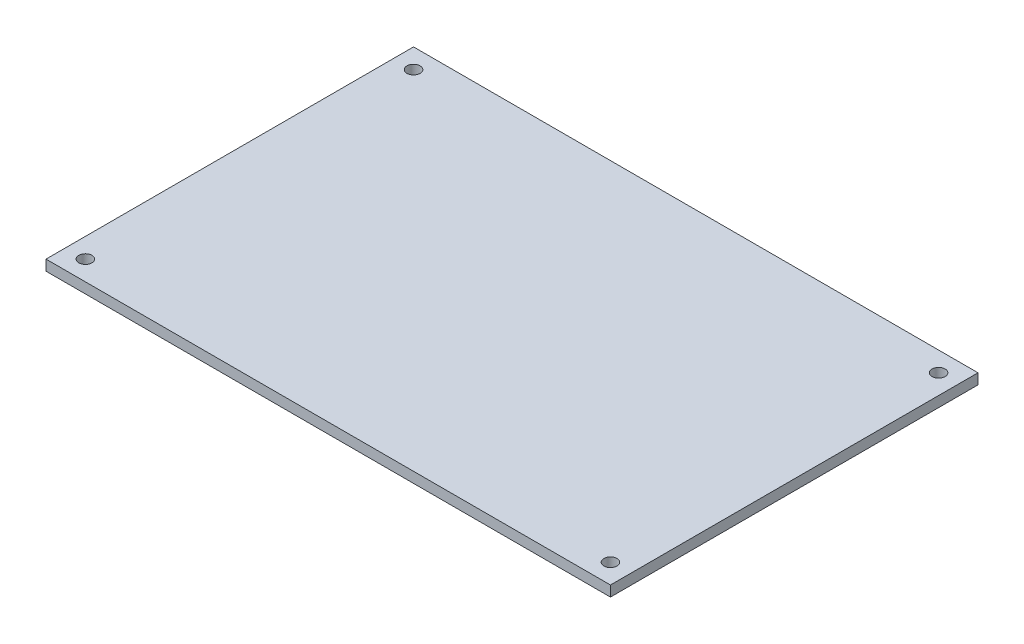
SolidWorks part; units mm, degrees
ref_plane "前视基准面" through (0, 0, 0) normal (0, 0, 1) x (1, 0, 0)
ref_plane "上视基准面" through (0, 0, 0) normal (0, 1, 0) x (1, 0, 0)
ref_plane "右视基准面" through (0, 0, 0) normal (1, 0, 0) x (0, 0, -1)
other "Configuration Table"
sketch "草图2" plane through (0, 0, 0) normal (0, 1, 0) x (1, 0, 0)
  line L0 (0, 28) -> (0, -28) construction
  line L1 (-43, -28) -> (43, -28)
  line L2 (-43, -28) -> (-43, 28)
  line L3 (-43, 28) -> (43, 28)
  line L4 (43, -28) -> (43, 28)
  line L5 (-43, -28) -> (43, 28) construction
  line L6 (-43, 28) -> (43, -28) construction
  line L7 (-43, 0) -> (43, 0) construction
  circle A0 centre (-40, 25) radius 1
  circle A1 centre (40, 25) radius 1
  circle A2 centre (40, -25) radius 1
  circle A3 centre (-40, -25) radius 1
  point P0 (0, 0)
  dimension "D3" = 2
  dimension "D1" = 86
  dimension "D2" = 56
  dimension "D4" = 3
  dimension "D5" = 3
extrude "凸台-拉伸1" add sketch "草图2" along normal blind 1.6
